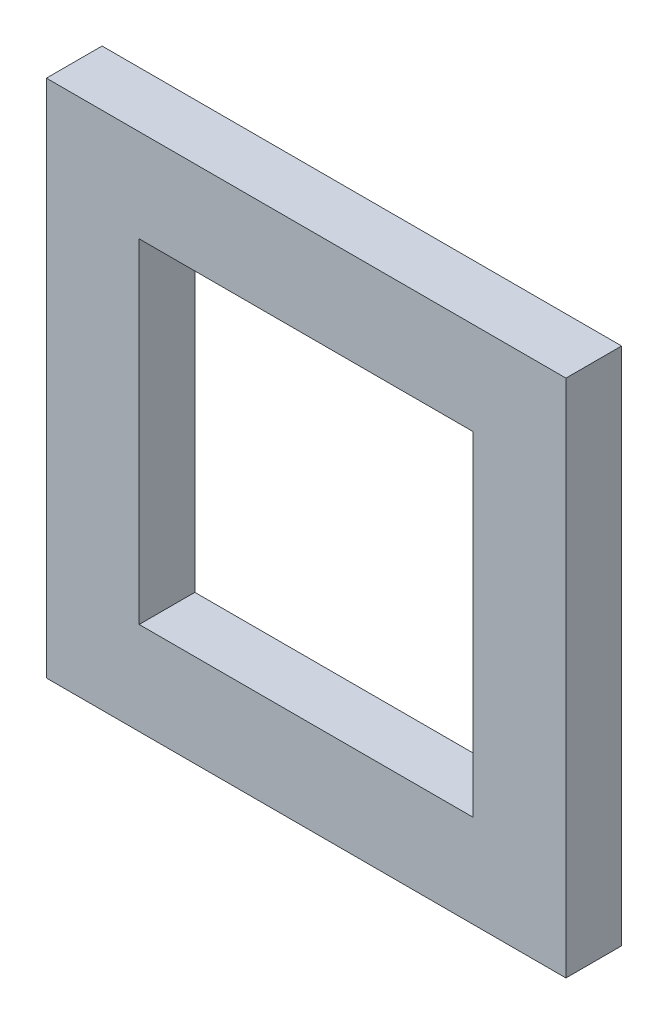
SolidWorks part; units mm, degrees
ref_plane "Front Plane" through (0, 0, 0) normal (0, 0, 1) x (1, 0, 0)
ref_plane "Top Plane" through (0, 0, 0) normal (0, 1, 0) x (1, 0, 0)
ref_plane "Right Plane" through (0, 0, 0) normal (1, 0, 0) x (0, 0, -1)
sketch "Sketch1" plane through (0, 0, 0) normal (0, 0, 1) x (1, 0, 0)
  line L1 (0, 0) -> (28, 0)
  line L2 (0, 0) -> (0, 28)
  line L3 (0, 28) -> (28, 28)
  line L4 (28, 0) -> (28, 28)
  line L6 (5, 5) -> (23, 5)
  line L7 (5, 5) -> (5, 23)
  line L8 (5, 23) -> (23, 23)
  line L9 (23, 5) -> (23, 23)
  dimension "D1" = 5
  dimension "D2" = 23
  dimension "D3" = 28
  dimension "D4" = 5
extrude "Profile" add sketch "Sketch1" along normal blind 3
equation "\"Profile_Depth\"= 3mm"
equation "\"D1@Profile\" = \"Profile_Depth\""
equation "\"Profile_Sketch_1\"= 5mm"
equation "\"D1@Sketch1\" = \"Profile_Sketch_1\""
equation "\"Profile_Sketch_2\"= 23mm"
equation "\"D2@Sketch1\" = \"Profile_Sketch_2\""
equation "\"Profile_Sketch_3\"= 28mm"
equation "\"D3@Sketch1\" = \"Profile_Sketch_3\""
equation "\"Profile_Sketch_4\"= 5mm"
equation "\"D4@Sketch1\" = \"Profile_Sketch_4\""
equation "\"EnvelopeWidth\"= 28mm"
equation "\"EnvelopeHeight\"= 28mm"
